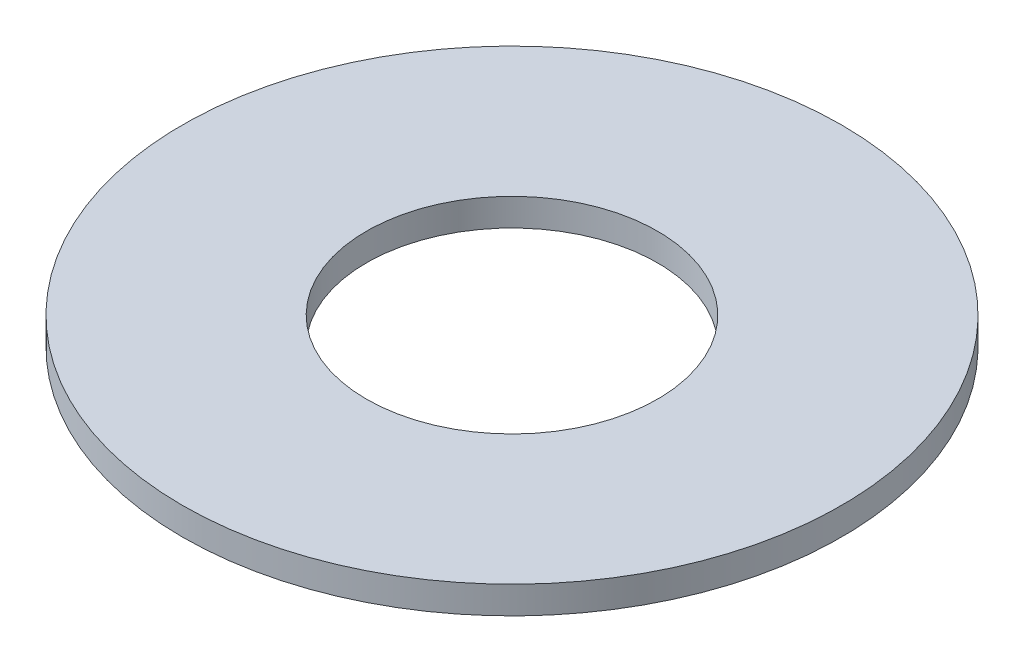
SolidWorks part; units mm, degrees
material "AISI Type A2 Tool Steel"
ref_plane "Front Plane" through (0, 0, 0) normal (0, 0, 1) x (1, 0, 0)
ref_plane "Top Plane" through (0, 0, 0) normal (0, 1, 0) x (1, 0, 0)
ref_plane "Right Plane" through (0, 0, 0) normal (1, 0, 0) x (0, 0, -1)
sketch "Sketch1" plane through (0, 0, 0) normal (0, 1, 0) x (1, 0, 0)
  circle A0 centre (0, 0) radius 2.65
  circle A1 centre (0, 0) radius 6
  dimension "D1" = 5.3
  dimension "D2" = 12
extrude "Boss-Extrude1" add sketch "Sketch1" along normal blind 0.5
